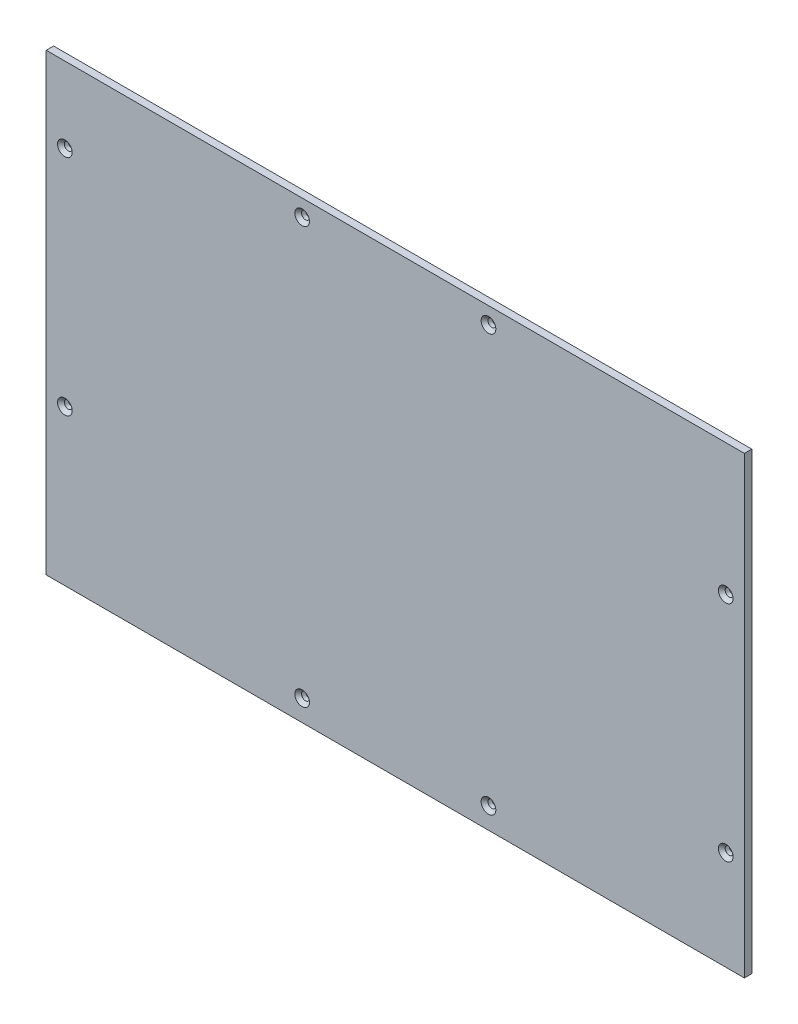
SolidWorks part; units mm, degrees
material "ABS"
ref_plane "X-Y Datum" through (0, 0, 0) normal (0, 0, 1) x (1, 0, 0)
ref_plane "X-Z Datum" through (0, 0, 0) normal (0, 1, 0) x (1, 0, 0)
ref_plane "Y-Z Datum" through (0, 0, 0) normal (1, 0, 0) x (0, 0, -1)
sketch "Sketch1" plane through (0, 0, 0) normal (0, 0, 1) x (1, 0, 0)
  line L0 (-149.85, 97.5219) -> (-149.85, -97.5219)
  line L1 (-149.85, 97.5219) -> (149.85, 97.5219)
  line L2 (-149.85, 97.5219) -> (-149.85, -97.5219)
  line L3 (-149.85, -97.5219) -> (149.85, -97.5219)
  line L4 (149.85, 97.5219) -> (149.85, -97.5219)
  line L5 (-149.85, 97.5219) -> (149.85, -97.5219) construction
  line L6 (-149.85, -97.5219) -> (149.85, 97.5219) construction
  line L7 (-149.85, -97.5219) -> (149.85, -97.5219)
  line L8 (149.85, 97.5219) -> (149.85, -97.5219)
  line L9 (-149.85, 97.5219) -> (149.85, 97.5219)
  circle A0 centre (-139.075, -86.7469) radius 10.775
  circle A1 centre (-115.075, -86.7469) radius 10.775 construction
  circle A2 centre (-127.075, -63.7469) radius 10.775
  point P0 (0, 0)
  dimension "D1" = 21.55
  dimension "D2" = 24
  dimension "D3" = 23
  dimension "D4" = 12
  dimension "D5" = 195.0437
  dimension "D6" = 299.7
  dimension "D7" = 0
extrude "Boss-Extrude1" add sketch "Sketch1" along normal blind 3.175 contours A0 L3 L4 L1 L2 A2 | A2 | A0 | A0 L2 L3 | L9 L0 L7 L8 L1 L4 L3 L2
sketch "Sketch2" plane through (0, 0, 3.175) normal (0, 0, 1) x (1, 0, 0)
  point P0 (40, -88.4276)
  point P1 (-40, -88.4276)
  point P3 (-141.85, -30.9219)
  point P5 (-141.85, 65.0781)
  point P7 (-40, 90.3781)
  point P9 (40, 90.3781)
  point P11 (141.85, 41.0781)
  point P13 (141.85, -54.9219)
hole_wizard "CSK for M3 Flat Head Machine Screw1" positions "Sketch5" profile "Sketch4" countersink size "M3" standard "ANSI Metric" end condition through all
sketch "Sketch5" plane through (0, 0, 3.175) normal (0, 0, 1) x (1, 0, 0)
  point P0 (-40, 90.3781)
  point P3 (40, 90.3781)
  point P6 (141.85, 41.0781)
  point P9 (141.85, -54.9219)
  point P12 (40, -88.4276)
  point P15 (-40, -88.4276)
  point P18 (-141.85, -30.9219)
  point P21 (-141.85, 65.0781)
sketch "Sketch4" plane through (-40, 90.3781, 3.175) normal (1, 0, 0) x (0, -1, 0)
  line L0 (0, 0) -> (0, 3.175)
  line L1 (0, 3.175) -> (1.7, 3.175)
  line L2 (1.7, 3.175) -> (1.7, 1.45)
  line L3 (1.7, 1.45) -> (3.15, 0)
  line L5 (3.15, 0) -> (0, 0)
  line L6 (-1.7, 1.45) -> (-3.15, 0) construction
  line L11 (0, -6.35) -> (0, 107.95) construction
  dimension "Thru Hole Dia." = 3.4
  dimension "Thru Hole Depth" = 3.175
  dimension "Near C'Sink Dia." = 6.3
  dimension "Near C'Sink Angle" = 90
